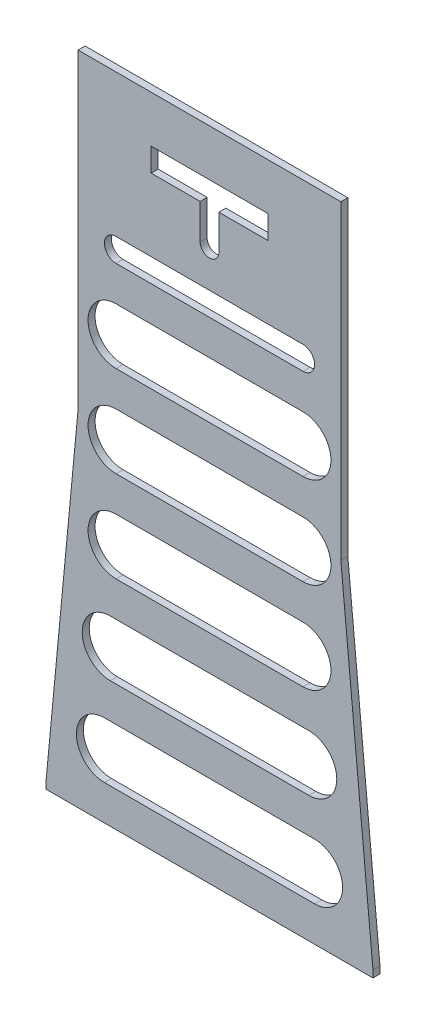
SolidWorks part; units mm, degrees
material "Teak"
ref_plane "Front Plane" through (0, 0, 0) normal (0, 0, 1) x (1, 0, 0)
ref_plane "Top Plane" through (0, 0, 0) normal (0, 1, 0) x (1, 0, 0)
ref_plane "Right Plane" through (0, 0, 0) normal (1, 0, 0) x (0, 0, -1)
sketch "Sketch1" plane through (0, 0, 0) normal (0, 0, 1) x (1, 0, 0)
  point P0 (0, 0)
  line B0 (40, -16) -> (-40, -16)
  line B1 (-40, -26) -> (40, -26)
  line B2 (-70, -236) -> (70, -236)
  line B3 (70, -236) -> (70, -233)
  line B4 (70, -233) -> (56.25, -88)
  line B5 (56.25, -88) -> (56.25, 45)
  line B6 (56.25, 45) -> (-56.25, 45)
  line B7 (-56.25, 45) -> (-56.25, -88)
  line B8 (-56.25, -88) -> (-70, -233)
  line B9 (-70, -233) -> (-70, -236)
  line B10 (25, 15) -> (25, 25)
  line B11 (4, 15) -> (25, 15)
  line B12 (4, 0) -> (4, 15)
  line B13 (-4, 15) -> (-4, 0)
  line B14 (-25, 15) -> (-4, 15)
  line B15 (-25, 25) -> (-25, 15)
  line B16 (25, 25) -> (-25, 25)
  line B17 (40, -41) -> (-40, -41)
  line B18 (-40, -65) -> (40, -65)
  line B19 (40, -80) -> (-40, -80)
  line B20 (-40, -104) -> (40, -104)
  line B21 (40, -119) -> (-40, -119)
  line B22 (-40, -143) -> (40, -143)
  line B23 (42.5, -158) -> (-42.5, -158)
  line B24 (-42.5, -182) -> (42.5, -182)
  line B25 (45, -197) -> (-45, -197)
  line B26 (-45, -221) -> (45, -221)
  arc B27 (-4, 0) -> (4, 0) centre (0, 0) ccw
  arc B28 (-40, -16) -> (-40, -26) centre (-40, -21) ccw
  arc B29 (40, -26) -> (40, -16) centre (40, -21) ccw
  arc B30 (-40, -41) -> (-40, -65) centre (-40, -53) ccw
  arc B31 (40, -65) -> (40, -41) centre (40, -53) ccw
  arc B32 (-40, -80) -> (-40, -104) centre (-40, -92) ccw
  arc B33 (40, -104) -> (40, -80) centre (40, -92) ccw
  arc B34 (-40, -119) -> (-40, -143) centre (-40, -131) ccw
  arc B35 (40, -143) -> (40, -119) centre (40, -131) ccw
  arc B36 (-42.5, -158) -> (-42.5, -182) centre (-42.5, -170) ccw
  arc B37 (42.5, -182) -> (42.5, -158) centre (42.5, -170) ccw
  arc B38 (-45, -197) -> (-45, -221) centre (-45, -209) ccw
  arc B39 (45, -221) -> (45, -197) centre (45, -209) ccw
sketch_block_instance "Block1-1"
sketch_block "Block1"
extrude "Boss-Extrude1" add sketch "Sketch1" along normal blind 3
